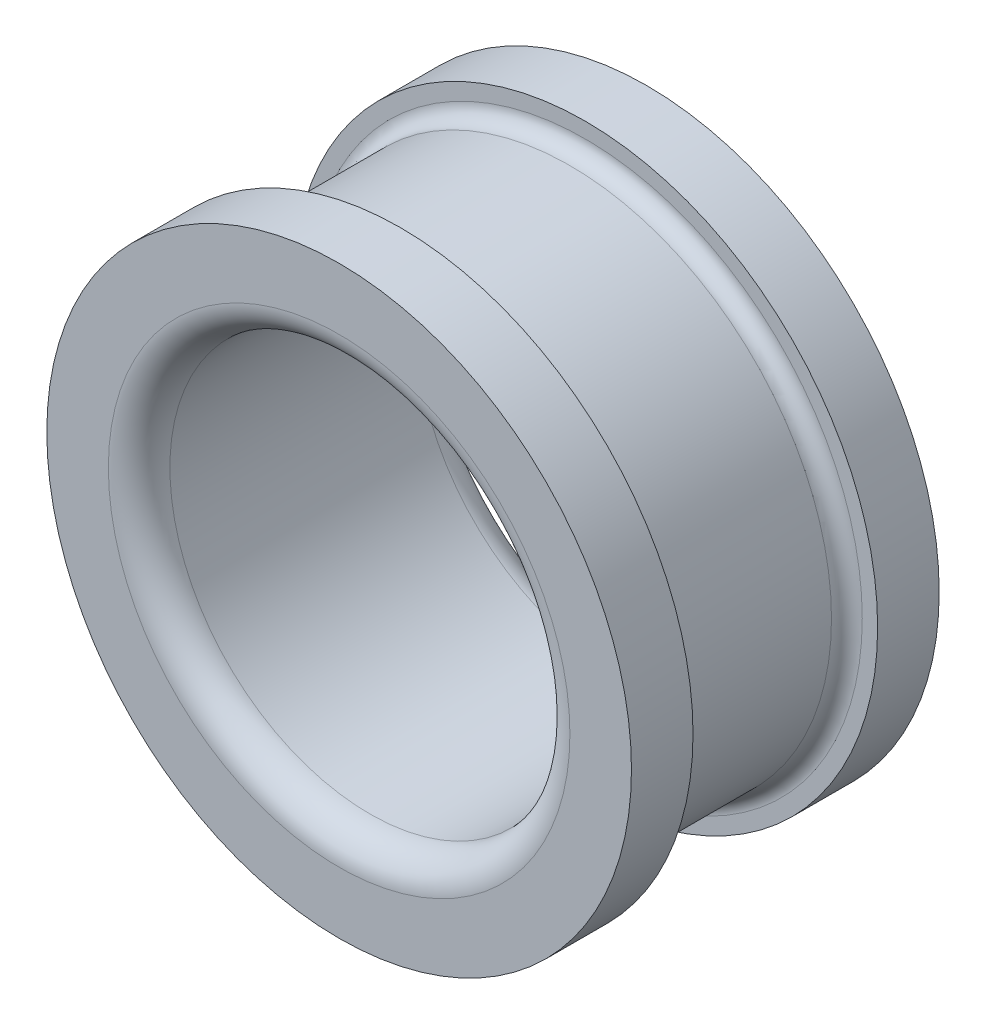
SolidWorks part; units mm, degrees
ref_plane "Front Plane" through (0, 0, 0) normal (0, 0, 1) x (1, 0, 0)
ref_plane "Top Plane" through (0, 0, 0) normal (0, 1, 0) x (1, 0, 0)
ref_plane "Right Plane" through (0, 0, 0) normal (1, 0, 0) x (0, 0, -1)
sketch "Sketch1" plane through (0, 0, 0) normal (0, 0, 1) x (1, 0, 0)
  circle A0 centre (0, 0) radius 9.5
  point P3 (0, 0)
  dimension "D1" = 19
extrude "Boss-Extrude1" add sketch "Sketch1" along normal blind 2
sketch "Sketch2" plane through (0, 0, 2) normal (0, 0, 1) x (1, 0, 0)
  circle A0 centre (0, 0) radius 8.5
  circle A1 centre (0, 0) radius 9.5 construction
  dimension "D1" = 1
extrude "Boss-Extrude2" add sketch "Sketch2" along normal blind 6
sketch "Sketch3" plane through (0, 0, 8) normal (0, 0, 1) x (1, 0, 0)
  circle A0 centre (0, 0) radius 9.5
extrude "Boss-Extrude3" add sketch "Sketch3" along normal blind 2
sketch "Sketch4" plane through (0, 0, 0) normal (0, 0, -1) x (-1, 0, 0)
  circle A0 centre (0, 0) radius 6.5
  dimension "D1" = 13
extrude "Cut-Extrude1" cut sketch "Sketch4" against normal through all both and the other way through all
fillet "Fillet1" radius 1 2 edges at (6.5, 0, 0) (-6.5, 0, 10)
fillet "Fillet2" radius 0.5 2 edges at (8.5, 0, 8) (8.5, 0, 2)
